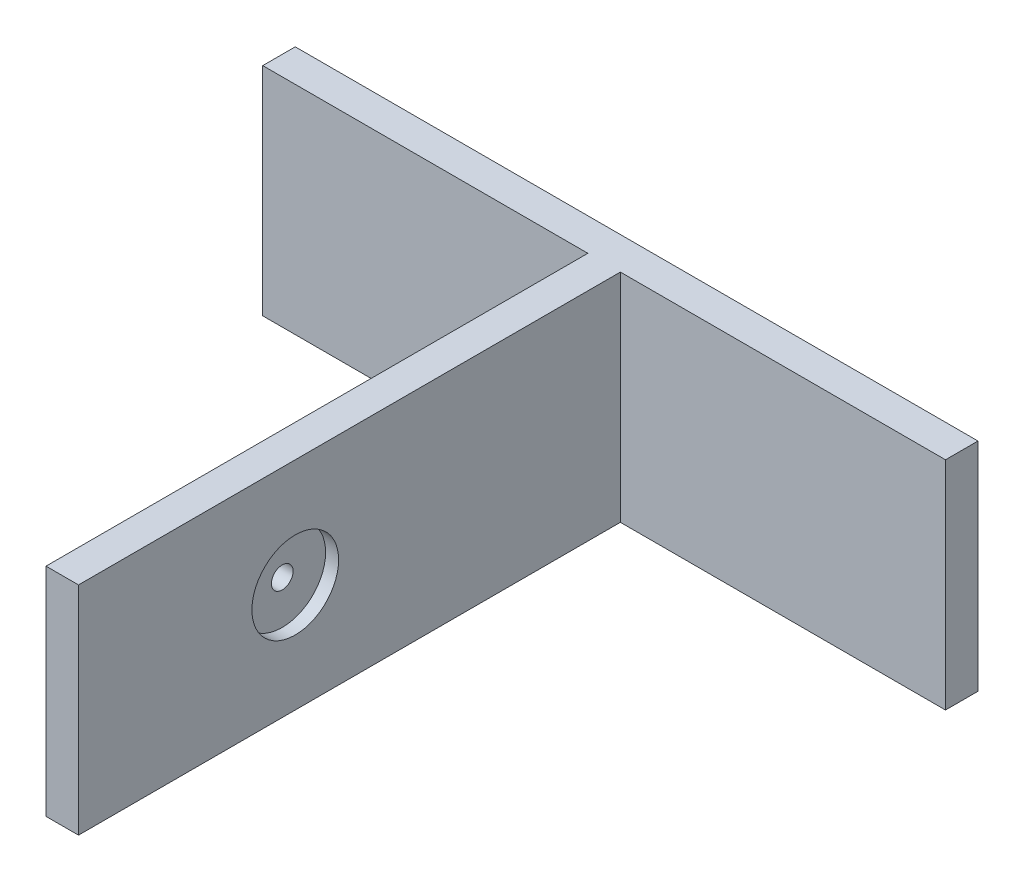
SolidWorks part; units mm, degrees
ref_plane "Alzado" through (0, 0, 0) normal (0, 0, 1) x (1, 0, 0)
ref_plane "Planta" through (0, 0, 0) normal (0, 1, 0) x (1, 0, 0)
ref_plane "Vista lateral" through (0, 0, 0) normal (1, 0, 0) x (0, 0, -1)
sketch "Croquis1" plane through (0, 0, 0) normal (0, 1, 0) x (1, 0, 0)
  line L0 (3.2166, -38.1976) -> (3.2166, 11.8024)
  line L1 (3.2166, 11.8024) -> (33.2166, 11.8024)
  line L2 (33.2166, 11.8024) -> (33.2166, 14.8024)
  line L3 (33.2166, 14.8024) -> (-29.7834, 14.8024)
  line L4 (-29.7834, 14.8024) -> (-29.7834, 11.8024)
  line L5 (-29.7834, 11.8024) -> (0.2166, 11.8024)
  line L6 (0.2166, 11.8024) -> (0.2166, -38.1976)
  line L7 (0.2166, -38.1976) -> (3.2166, -38.1976)
extrude "Saliente-Extruir1" add sketch "Croquis1" along normal blind 20
sketch "Croquis2" plane through (3.2166, 0, 0) normal (1, 0, 0) x (0, 0, -1)
  circle A0 centre (-18.1976, 10) radius 4
extrude "Cortar-Extruir1" cut sketch "Croquis2" against normal blind 1.2
sketch "Croquis3" plane through (2.0166, 0, 0) normal (1, 0, 0) x (0, 0, -1)
  circle A0 centre (-18.1976, 10) radius 1
extrude "Cortar-Extruir2" cut sketch "Croquis3" against normal blind 1.8
sketch "Croquis5" plane through (0, 0, -14.8024) normal (0, 0, -1) x (-1, 0, 0)
  circle A0 centre (-1.7166, 10) radius 1
extrude "Saliente-Extruir2" add sketch "Croquis5" along normal blind 1
